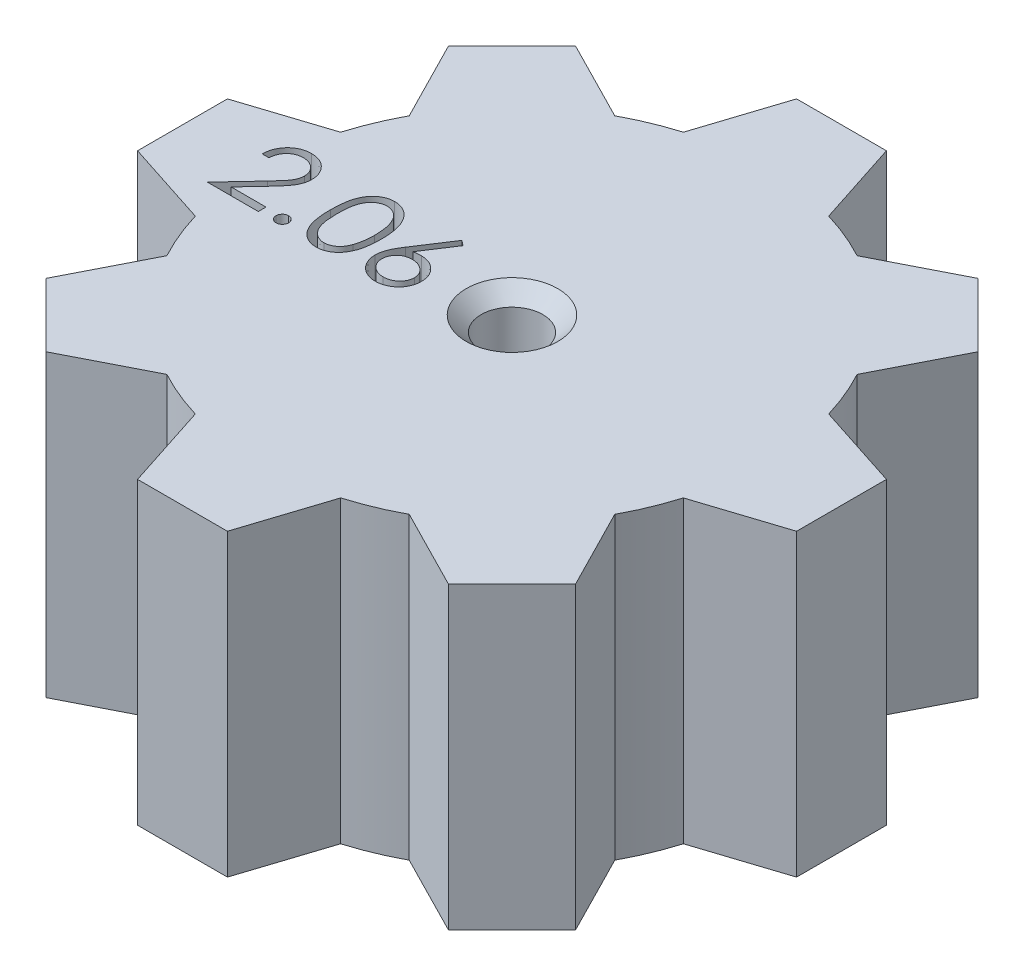
SolidWorks part; units mm, degrees
ref_plane "Front Plane" through (0, 0, 0) normal (0, 0, 1) x (1, 0, 0)
ref_plane "Top Plane" through (0, 0, 0) normal (0, 1, 0) x (1, 0, 0)
ref_plane "Right Plane" through (0, 0, 0) normal (1, 0, 0) x (0, 0, -1)
sketch "Sketch1" plane through (0, 0, 0) normal (0, 1, 0) x (1, 0, 0)
  line L1 (-0.25, 4.2426) -> (0.25, 4.2426) construction
  line L39 (0, 8.5) -> (0, 11) construction
  line L40 (-1.5, 11) -> (1.5, 11)
  line L41 (-1.5, 11) -> (-2.4259, 8.1465)
  line L42 (1.5, 11) -> (2.4259, 8.1465)
  line L43 (6.7175, 8.8388) -> (4.045, 7.4758)
  line L44 (6.7175, 8.8388) -> (8.8388, 6.7175)
  line L45 (8.8388, 6.7175) -> (7.4758, 4.045)
  line L46 (11, 1.5) -> (8.1465, 2.4259)
  line L47 (11, 1.5) -> (11, -1.5)
  line L48 (11, -1.5) -> (8.1465, -2.4259)
  line L49 (8.8388, -6.7175) -> (7.4758, -4.045)
  line L50 (8.8388, -6.7175) -> (6.7175, -8.8388)
  line L51 (6.7175, -8.8388) -> (4.045, -7.4758)
  line L52 (1.5, -11) -> (2.4259, -8.1465)
  line L53 (1.5, -11) -> (-1.5, -11)
  line L54 (-1.5, -11) -> (-2.4259, -8.1465)
  line L55 (-6.7175, -8.8388) -> (-4.045, -7.4758)
  line L56 (-6.7175, -8.8388) -> (-8.8388, -6.7175)
  line L57 (-8.8388, -6.7175) -> (-7.4758, -4.045)
  line L58 (-11, -1.5) -> (-8.1465, -2.4259)
  line L59 (-11, -1.5) -> (-11, 1.5)
  line L60 (-11, 1.5) -> (-8.1465, 2.4259)
  line L61 (-8.8388, 6.7175) -> (-7.4758, 4.045)
  line L62 (-8.8388, 6.7175) -> (-6.7175, 8.8388)
  line L63 (-6.7175, 8.8388) -> (-4.045, 7.4758)
  circle A0 centre (0, 0) radius 1.03
  circle A1 centre (0, 0) radius 5.25 construction
  circle A14 centre (0, 0) radius 8.5 construction
  arc A15 (2.4259, 8.1465) -> (4.045, 7.4758) centre (0, 0) cw
  arc A16 (7.4758, 4.045) -> (8.1465, 2.4259) centre (0, 0) cw
  arc A17 (8.1465, -2.4259) -> (7.4758, -4.045) centre (0, 0) cw
  arc A18 (4.045, -7.4758) -> (2.4259, -8.1465) centre (0, 0) cw
  arc A19 (-2.4259, -8.1465) -> (-4.045, -7.4758) centre (0, 0) cw
  arc A20 (-7.4758, -4.045) -> (-8.1465, -2.4259) centre (0, 0) cw
  arc A21 (-8.1465, 2.4259) -> (-7.4758, 4.045) centre (0, 0) cw
  arc A22 (-4.045, 7.4758) -> (-2.4259, 8.1465) centre (0, 0) cw
  point P31 (0, 0)
  point P60 (0, 0)
  point P71 (0, 11)
  point P105 (0, 0)
  dimension "D1" = 2.06
  dimension "D2" = 10.5
  dimension "D5" = 17
  dimension "D6" = 2.5
  dimension "D7" = 3
  dimension "D8" = 3
  dimension "D9" = 8
extrude "Boss-Extrude1" add sketch "Sketch1" along normal blind 10
sketch "Sketch2" plane through (0, 10, 0) normal (0, 1, 0) x (1, 0, 0)
  text T0 "2.06" font "Century Gothic" height 2.5
extrude "Cut-Extrude1" cut sketch "Sketch2" against normal blind 1
chamfer "Chamfer1" distance 0.5 angle 45 1 edges at (0, 10, 1.03)
